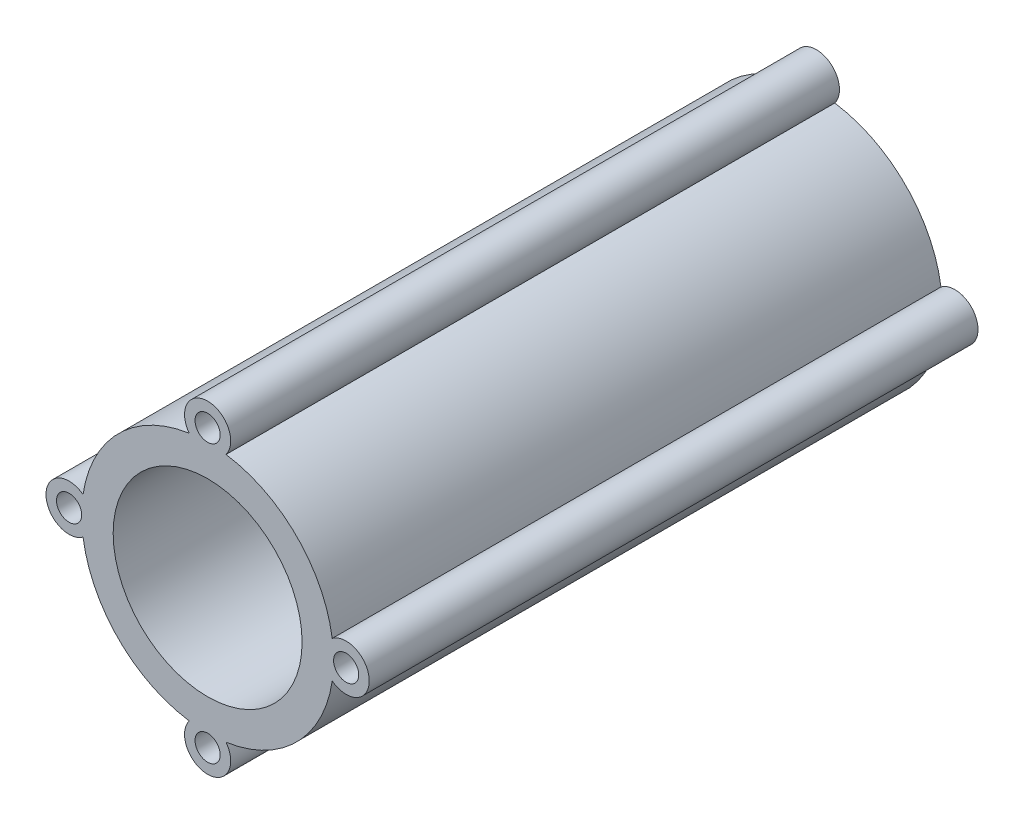
SolidWorks part; units mm, degrees
material "6063-O"
ref_plane "Front Plane" through (0, 0, 0) normal (0, 0, 1) x (1, 0, 0)
ref_plane "Top Plane" through (0, 0, 0) normal (0, 1, 0) x (1, 0, 0)
ref_plane "Right Plane" through (0, 0, 0) normal (1, 0, 0) x (0, 0, -1)
sketch "Sketch1" plane through (0, 0, 0) normal (0, 0, 1) x (1, 0, 0)
  circle A0 centre (0, 0) radius 22.5
  circle A1 centre (0, 0) radius 30
  point P8 (-0.0771, 33.3907)
  point P11 (-0.0771, 33.3907)
  point P15 (0, 0)
  point P20 (0, 0)
  point P22 (-0.2523, -5.2973)
  point P23 (-0.0168, -0.3532)
  point P26 (0, 0)
  dimension "D1" = 45
  dimension "D2" = 60
extrude "Boss-Extrude2" add sketch "Sketch1" along normal blind 145
sketch "Croquis1" plane through (0, 0, 0) normal (0, 0, 1) x (1, 0, 0)
  line L0 (-33, 0) -> (0, 0)
  circle A0 centre (0, 0) radius 30
  circle A1 centre (-33, 0) radius 5.5
  circle A2 centre (-33, 0) radius 3
  dimension "D1" = 60
  dimension "D3" = 6
  dimension "D4" = 33
extrude "Saliente-Extruir1" add sketch "Croquis1" along normal blind 145 contours A2 | A1
pattern_circular "MatrizC1" count 4 over 360 about axis through (0, 0, 0) along (0, 0, 1) of "Saliente-Extruir1"
equation "\"20°°\"=45"
